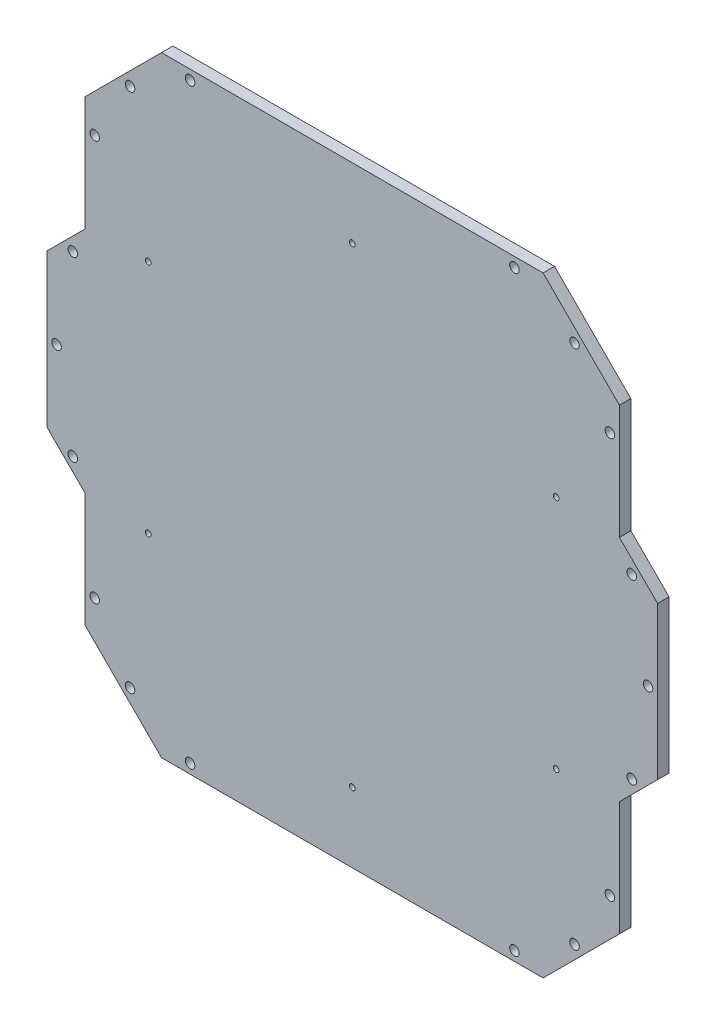
SolidWorks part; units mm, degrees
ref_plane "Front Plane" through (0, 0, 0) normal (0, 0, 1) x (1, 0, 0)
ref_plane "Top Plane" through (0, 0, 0) normal (0, 1, 0) x (1, 0, 0)
ref_plane "Right Plane" through (0, 0, 0) normal (1, 0, 0) x (0, 0, -1)
sketch "Model" plane through (0, 0, 0) normal (0, 0, 1) x (1, 0, 0)
  line L0 (41.0576, 7.1988) -> (141.0576, 7.1988)
  line L1 (141.0576, 7.1988) -> (161.0576, 27.1988)
  line L2 (41.0576, 167.1988) -> (141.0576, 167.1988)
  line L3 (141.0576, 167.1988) -> (161.0576, 147.1988)
  line L4 (41.0576, 7.1988) -> (21.0576, 27.1988)
  line L5 (11.0576, 67.1988) -> (11.0576, 107.1988)
  line L6 (41.0576, 167.1988) -> (21.0576, 147.1988)
  line L7 (21.0576, 27.1988) -> (21.0576, 57.1988)
  line L8 (11.0576, 67.1988) -> (21.0576, 57.1988)
  line L9 (21.0576, 147.1988) -> (21.0576, 117.1988)
  line L10 (11.0576, 107.1988) -> (21.0576, 117.1988)
  line L11 (171.0576, 67.1988) -> (171.0576, 107.1988)
  line L12 (161.0576, 27.1988) -> (161.0576, 57.1988)
  line L13 (171.0576, 67.1988) -> (161.0576, 57.1988)
  line L14 (161.0576, 147.1988) -> (161.0576, 117.1988)
  line L15 (171.0576, 107.1988) -> (161.0576, 117.1988)
  circle A0 centre (133.5576, 9.6988) radius 1.25
  circle A1 centre (158.5576, 34.6988) radius 1.25
  circle A2 centre (149.2898, 18.9665) radius 1.25
  circle A3 centre (48.5576, 9.6988) radius 1.25
  circle A4 centre (23.5576, 34.6988) radius 1.25
  circle A5 centre (32.8254, 18.9665) radius 1.25
  circle A6 centre (133.5576, 164.6988) radius 1.25
  circle A7 centre (158.5576, 139.6988) radius 1.25
  circle A8 centre (149.2898, 155.431) radius 1.25
  circle A9 centre (48.5576, 164.6988) radius 1.25
  circle A10 centre (23.5576, 139.6988) radius 1.25
  circle A11 centre (32.8254, 155.431) radius 1.25
  circle A12 centre (17.8254, 63.9665) radius 1.25
  circle A13 centre (13.5576, 87.1988) radius 1.25
  circle A14 centre (17.8254, 110.431) radius 1.25
  circle A15 centre (164.2898, 63.9665) radius 1.25
  circle A16 centre (168.5576, 87.1988) radius 1.25
  circle A17 centre (164.2898, 110.431) radius 1.25
extrude "Boss-Extrude1" add sketch "Model" along normal blind 3
sketch "Sketch1" plane through (0, 0, 3) normal (0, 0, 1) x (1, 0, 0)
  line L0 (91.0576, 167.1988) -> (91.0576, 7.1988) construction
  line L1 (141.0576, 167.1988) -> (41.0576, 167.1988) construction
  line L2 (41.0576, 7.1988) -> (141.0576, 7.1988) construction
  line L3 (11.0576, 87.1988) -> (171.0576, 87.1988) construction
  line L4 (11.0576, 107.1988) -> (11.0576, 67.1988) construction
  line L5 (171.0576, 67.1988) -> (171.0576, 107.1988) construction
  line L7 (91.0576, 148.9116) -> (37.6128, 118.0552) construction
  line L8 (37.6128, 118.0552) -> (37.6128, 56.3424) construction
  line L9 (37.6128, 56.3424) -> (91.0576, 25.486) construction
  line L10 (91.0576, 25.486) -> (144.5025, 56.3424) construction
  line L11 (144.5025, 56.3424) -> (144.5025, 118.0552) construction
  line L12 (144.5025, 118.0552) -> (91.0576, 148.9116) construction
  circle A0 centre (91.0576, 148.9116) radius 0.75
  circle A1 centre (37.6128, 118.0552) radius 0.75
  circle A2 centre (144.5025, 118.0552) radius 0.75
  circle A3 centre (144.5025, 56.3424) radius 0.75
  circle A4 centre (91.0576, 25.486) radius 0.75
  circle A5 centre (37.6128, 56.3424) radius 0.75
  dimension "D1" = 1.5
extrude "Cut-Extrude1" cut sketch "Sketch1" against normal blind 10
